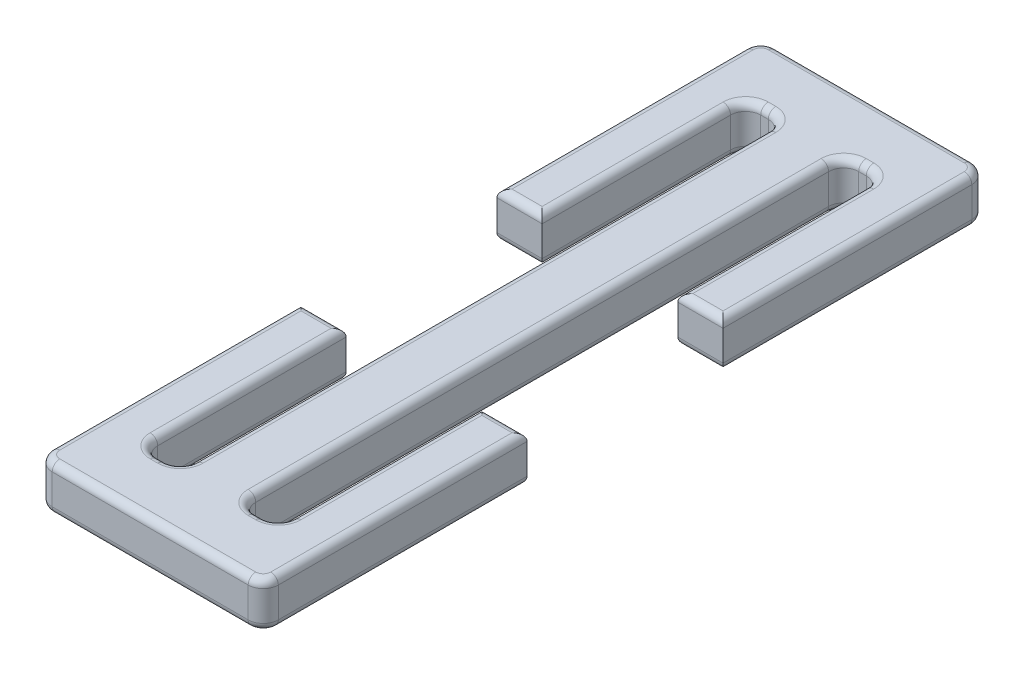
SolidWorks part; units mm, degrees
ref_plane "Front Plane" through (0, 0, 0) normal (0, 0, 1) x (1, 0, 0)
ref_plane "Top Plane" through (0, 0, 0) normal (0, 1, 0) x (1, 0, 0)
ref_plane "Right Plane" through (0, 0, 0) normal (1, 0, 0) x (0, 0, -1)
sketch "Sketch1" plane through (0, 0, 0) normal (0, 1, 0) x (1, 0, 0)
  line L1 (-7.5, -24) -> (7.5, -24)
  line L2 (-7.5, -24) -> (-7.5, 24)
  line L3 (-7.5, 24) -> (7.5, 24)
  line L4 (7.5, -24) -> (7.5, 24)
  line L5 (-7.5, -24) -> (7.5, 24) construction
  line L6 (-7.5, 24) -> (7.5, -24) construction
  line L7 (-4.5, -20) -> (4.5, -20)
  line L8 (-4.5, -20) -> (-4.5, 20)
  line L9 (-4.5, 20) -> (4.5, 20)
  line L10 (4.5, -20) -> (4.5, 20)
  line L11 (-4.5, -20) -> (4.5, 20) construction
  line L12 (-4.5, 20) -> (4.5, -20) construction
  line L13 (-2, 20) -> (2, 20)
  line L14 (-2, 20) -> (-2, -20)
  line L15 (-2, -20) -> (2, -20)
  line L16 (2, 20) -> (2, -20)
  line L17 (-2, 20) -> (2, -20) construction
  line L18 (-2, -20) -> (2, 20) construction
  line L19 (4.5, -6.5) -> (7.5, -6.5)
  line L20 (4.5, -6.5) -> (4.5, 6.5)
  line L21 (4.5, 6.5) -> (7.5, 6.5)
  line L22 (7.5, -6.5) -> (7.5, 6.5)
  line L23 (4.5, -6.5) -> (7.5, 6.5) construction
  line L24 (4.5, 6.5) -> (7.5, -6.5) construction
  line L25 (-4.5, -6.5) -> (-7.5, -6.5)
  line L26 (-4.5, -6.5) -> (-4.5, 6.5)
  line L27 (-4.5, 6.5) -> (-7.5, 6.5)
  line L28 (-7.5, -6.5) -> (-7.5, 6.5)
  line L29 (-4.5, -6.5) -> (-7.5, 6.5) construction
  line L30 (-4.5, 6.5) -> (-7.5, -6.5) construction
  point P0 (0, 0)
  point P6 (0, 0)
  point P11 (0, 0)
  point P16 (6, 0)
  point P21 (-6, 0)
  point P26 (0, 0)
  point P27 (0, 0)
  point P28 (0, 0)
  dimension "D1" = 3
  dimension "D2" = 4
  dimension "D3" = 4
  dimension "D4" = 2.5
  dimension "D5" = 40
  dimension "D6" = 13
  dimension "D7" = 13
extrude "Boss-Extrude1" add sketch "Sketch1" along normal blind 3 contours L27 L8 L9 L10 L21 L4 L3 L2 | L8 L25 L2 L1 L4 L19 L10 L7 | L16 L9 L14 L7
fillet "Fillet1" radius 1 12 edges at (4.5, 1.5, -20) (4.5, 1.5, 20) (2, 1.5, 20) (-2, 1.5, -20) (-2, 1.5, 20) (-4.5, 1.5, 20) (-4.5, 1.5, -20) (2, 1.5, -20) (-7.5, 1.5, 24) (-7.5, 1.5, -24) (7.5, 1.5, -24) (7.5, 1.5, 24)
fillet "Fillet2" radius 0.5 64 edges at (7.2071, 0, 23.7071) (7.5, 0, 14.75) (6, 0, 6.5) (4.5, 0, 12.75) (4.2071, 0, 19.7071) (3.25, 0, 20) (2.2929, 0, 19.7071) (2, 0, 0) (2.2929, 0, -19.7071) (3.25, 0, -20) (4.2071, 0, -19.7071) (4.5, 0, -12.75) (6, 0, -6.5) (7.5, 0, -14.75) (7.2071, 0, -23.7071) (0, 0, -24) (-7.2071, 0, -23.7071) (-7.5, 0, -14.75) (-6, 0, -6.5) (-4.5, 0, -12.75) (-4.2071, 0, -19.7071) (-3.25, 0, -20) (-2.2929, 0, -19.7071) (-2, 0, 0) (-2.2929, 0, 19.7071) (-3.25, 0, 20) (-4.2071, 0, 19.7071) (-4.5, 0, 12.75) (-6, 0, 6.5) (-7.5, 0, 14.75) (-7.2071, 0, 23.7071) (0, 0, 24) (-6, 3, 6.5) (-4.5, 3, 12.75) (-4.2071, 3, 19.7071) (-3.25, 3, 20) (-2.2929, 3, 19.7071) (-2, 3, 0) (-2.2929, 3, -19.7071) (-3.25, 3, -20) (-4.2071, 3, -19.7071) (-4.5, 3, -12.75) (-6, 3, -6.5) (-7.5, 3, -14.75) (-7.2071, 3, -23.7071) (0, 3, -24) (7.2071, 3, -23.7071) (7.5, 3, -14.75) (6, 3, -6.5) (4.5, 3, -12.75) (4.2071, 3, -19.7071) (3.25, 3, -20) (2.2929, 3, -19.7071) (2, 3, 0) (2.2929, 3, 19.7071) (3.25, 3, 20) (4.2071, 3, 19.7071) (4.5, 3, 12.75) (6, 3, 6.5) (7.5, 3, 14.75) (7.2071, 3, 23.7071) (0, 3, 24) (-7.2071, 3, 23.7071) (-7.5, 3, 14.75)
